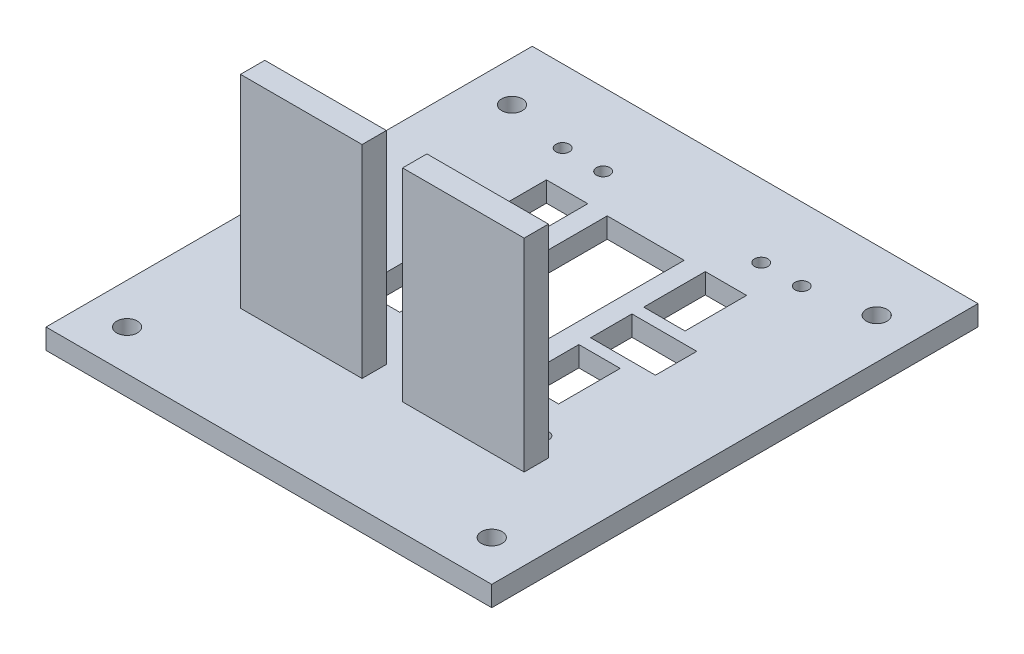
SolidWorks part; units mm, degrees
ref_plane "Front Plane" through (0, 0, 0) normal (0, 0, 1) x (1, 0, 0)
ref_plane "Top Plane" through (0, 0, 0) normal (0, 1, 0) x (1, 0, 0)
ref_plane "Right Plane" through (0, 0, 0) normal (1, 0, 0) x (0, 0, -1)
sketch "Sketch1" plane through (0, 0, 0) normal (0, 1, 0) x (1, 0, 0)
  line L0 (0, 0) -> (9.5, 0) construction
  line L1 (-55, 70) -> (55, 70)
  line L2 (-55, 70) -> (-55, -70)
  line L3 (-55, -70) -> (55, -70)
  line L4 (55, 70) -> (55, -70)
  line L5 (-55, 70) -> (55, -70) construction
  line L6 (-55, -70) -> (55, 70) construction
  line L7 (-9.5, 23) -> (9.5, 23)
  line L8 (-9.5, 23) -> (-9.5, -23)
  line L9 (-9.5, -23) -> (9.5, -23)
  line L10 (9.5, 23) -> (9.5, -23)
  line L11 (-9.5, 23) -> (9.5, -23) construction
  line L12 (-9.5, -23) -> (9.5, 23) construction
  line L14 (0, 0) -> (0, 35.7746) construction
  line L17 (-55, -70) -> (-20, -70)
  line L18 (-55, -70) -> (-55, -31.75)
  line L22 (-55, 70) -> (55, 70)
  line L23 (-55, 70) -> (-55, 50)
  line L24 (-55, 50) -> (55, 50)
  line L25 (55, 70) -> (55, 50)
  line L31 (-55, 31.75) -> (-55, -31.75)
  line L35 (55, 31.75) -> (55, -31.75)
  line L36 (-20, 70) -> (20, 70)
  line L40 (-20, -70) -> (20, -70)
  line L46 (2.5, -70) -> (42.5, -70)
  circle A1 centre (29.5, 32) radius 1.65
  circle A2 centre (19.5, 32) radius 1.65
  circle A3 centre (19.5, -32) radius 1.65
  circle A4 centre (29.5, -32) radius 1.65
  circle A5 centre (-29.5, -32) radius 1.65
  circle A6 centre (-19.5, -32) radius 1.65
  circle A7 centre (-19.5, 32) radius 1.65
  circle A8 centre (-29.5, 32) radius 1.65
  point P0 (0, 0)
  point P6 (0, 0)
  point P13 (0, 0)
  dimension "D5" = 9
  dimension "D8" = 20
  dimension "D9" = 20
  dimension "D6" = 3.3
  dimension "D1" = 140
  dimension "D2" = 110
  dimension "D3" = 46
  dimension "D4" = 19
  dimension "D7" = 2
extrude "Boss-Extrude3" add sketch "Sketch1" along normal blind 5
sketch "Sketch5" plane through (0, 0, 0) normal (0, -1, 0) x (1, 0, 0)
  line L0 (-55, 70) -> (55, 70) construction
  line L1 (-55, -50) -> (-55, 70) construction
  line L2 (-55, -50) -> (55, -50) construction
  line L3 (0, 0) -> (0, -67.3907) construction
  circle A0 centre (-45, 60) radius 2.55
  circle A1 centre (-45, -35) radius 2.55
  circle A2 centre (45, -35) radius 2.55
  circle A3 centre (45, 60) radius 2.55
  dimension "D1" = 5.1
  dimension "D3" = 10
  dimension "D4" = 5.1
  dimension "D6" = 10
  dimension "D2" = 10
  dimension "D5" = 15
extrude "Cut-Extrude2" cut sketch "Sketch5" against normal through all
sketch "Sketch9" plane through (0, 5, 0) normal (0, 1, 0) x (1, 0, 0)
  line L0 (0, 0) -> (0, -16.1548) construction
  line L1 (-9.5, 23) -> (9.5, 23)
  line L2 (-9.5, 23) -> (-9.5, -23)
  line L3 (-9.5, -23) -> (9.5, -23)
  line L4 (9.5, 23) -> (9.5, -23)
  line L5 (-9.5, 23) -> (9.5, -23) construction
  line L6 (-9.5, -23) -> (9.5, 23) construction
  line L7 (-14.5, 23.2) -> (-24.7, 23.2)
  line L8 (-14.5, 23.2) -> (-14.5, -23.2)
  line L9 (-14.5, -23.2) -> (-24.7, -23.2)
  line L10 (-24.7, 23.2) -> (-24.7, -23.2)
  line L11 (-24.7, 8) -> (-14.5, 8)
  line L12 (-24.7, -8) -> (-14.5, -8)
  line L13 (24.7, -8) -> (14.5, -8)
  line L14 (24.7, 8) -> (14.5, 8)
  line L15 (24.7, 23.2) -> (24.7, -23.2)
  line L16 (14.5, -23.2) -> (24.7, -23.2)
  line L17 (14.5, 23.2) -> (14.5, -23.2)
  line L18 (14.5, 23.2) -> (24.7, 23.2)
  point P0 (0, 0)
  dimension "D1" = 5
  dimension "D2" = 10.2
  dimension "D3" = 0.2
  dimension "D4" = 0.2
  dimension "D5" = 15.2
  dimension "D6" = 15.2
extrude "Cut-Extrude3" cut sketch "Sketch9" against normal through all contours L10 L11 L8 L7 | L12 L10 L9 L8 | L13 L17 L16 L15 | L18 L17 L14 L15
sketch "Sketch6" plane through (0, 5, 0) normal (0, 1, 0) x (1, 0, 0)
  line L6 (-9.5, -23) -> (9.5, -23) construction
  line L8 (-35, -36) -> (35, -36)
  line L9 (-35, -36) -> (-35, -42)
  line L10 (-35, -42) -> (35, -42)
  line L11 (35, -36) -> (35, -42)
  line L14 (-9.5, 23) -> (-9.5, -23) construction
  line L15 (5, -36) -> (-5, -36)
  line L16 (5, -36) -> (5, -42)
  line L17 (5, -42) -> (-5, -42)
  line L18 (-5, -36) -> (-5, -42)
  line L19 (9.5, 23) -> (9.5, -23) construction
  dimension "D1" = 13
  dimension "D2" = 6
  dimension "D3" = 4.5
  dimension "D4" = 4.5
  dimension "D5" = 30
  dimension "D6" = 30
extrude "Boss-Extrude4" add sketch "Sketch6" along normal blind 50 contours L18 L8 L9 L10 | L8 L16 L10 L11
sketch "Sketch11" plane through (0, 5, 0) normal (0, 1, 0) x (1, 0, 0)
  line L0 (9.5, 23) -> (9.5, -23) construction
  line L1 (14.5, 5.1) -> (30.5, 5.1)
  line L2 (14.5, 5.1) -> (14.5, -5.1)
  line L3 (14.5, -5.1) -> (30.5, -5.1)
  line L4 (30.5, 5.1) -> (30.5, -5.1)
  line L5 (-9.5, -23) -> (9.5, -23) construction
  line L6 (-9.5, 23) -> (9.5, 23) construction
  dimension "D1" = 5
  dimension "D2" = 16
  dimension "D3" = 17.9
  dimension "D4" = 17.9
extrude "Cut-Extrude4" cut sketch "Sketch11" against normal through all
